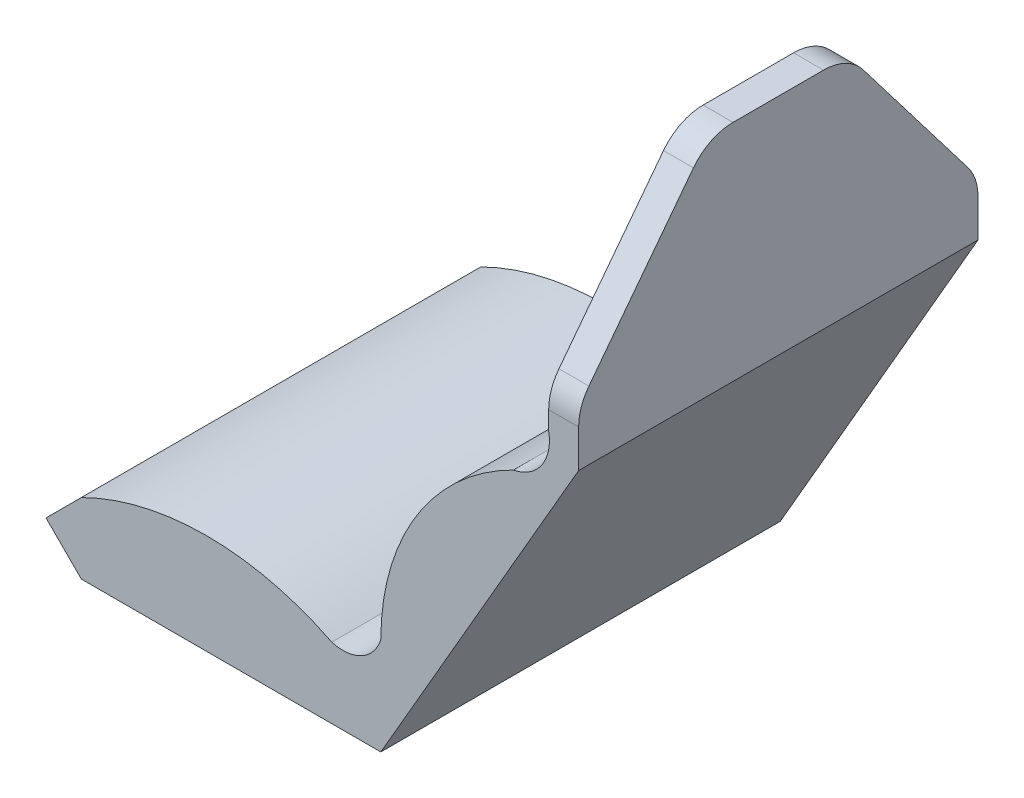
SolidWorks part; units mm, degrees
ref_plane "Front Plane" through (0, 0, 0) normal (0, 0, 1) x (1, 0, 0)
ref_plane "Top Plane" through (0, 0, 0) normal (0, 1, 0) x (1, 0, 0)
ref_plane "Right Plane" through (0, 0, 0) normal (1, 0, 0) x (0, 0, -1)
sketch "Sketch1" plane through (0, 0, 0) normal (0, 0, 1) x (1, 0, 0)
  line L0 (0, 0) -> (-300, 0)
  line L1 (-300, 0) -> (-335.3553, 35.3553)
  line L2 (-335.3553, 35.3553) -> (-300, 70.7107)
  line L5 (168.1185, 362.4009) -> (168.1185, 567.8648)
  line L6 (168.1185, 567.8648) -> (198.1185, 567.8648)
  line L7 (198.1185, 567.8648) -> (198.1185, 343.1513)
  line L8 (198.1185, 343.1513) -> (0, 0)
  arc A0 (-300, 70.7107) -> (-49.0797, 70.7107) centre (-174.5398, -179.851) cw
  arc A1 (-49.0797, 70.7107) -> (0, 97.6492) centre (-38.0091, 108.7198) ccw
  arc A2 (0, 97.6492) -> (132.8422, 310.9725) centre (238.2214, 97.3262) cw
  arc A3 (132.8422, 310.9725) -> (168.1185, 362.4009) centre (124.7661, 354.3249) ccw
  dimension "D1" = 300
  dimension "D2" = 50
  dimension "D3" = 50
  dimension "D4" = 60
  dimension "D6" = 30
extrude "Boss-Extrude1" add sketch "Sketch1" against normal blind 200
mirror "Mirror1" about plane through (-174.5398, -179.851, -200) normal (0, 0, -1) of bodies 101
chamfer "Chamfer1" distance 130 distance2 170 1 edges at (183.1185, 567.8648, 0)
chamfer "Chamfer2" distance 170 distance2 130 1 edges at (183.1185, 567.8648, -400)
fillet "Fillet1" radius 50 4 edges at (183.1185, 397.8648, -400) (183.1185, 397.8648, 0) (183.1185, 567.8648, -270) (183.1185, 567.8648, -130)
sketch "Sketch2" plane through (0, 0, 0) normal (0, -1, 0) x (1, 0, 0)
  circle A0 centre (-150, -200) radius 20
  dimension "D1" = 40
extrude "Boss-Extrude2" add sketch "Sketch2" along normal blind 10 contours A0
